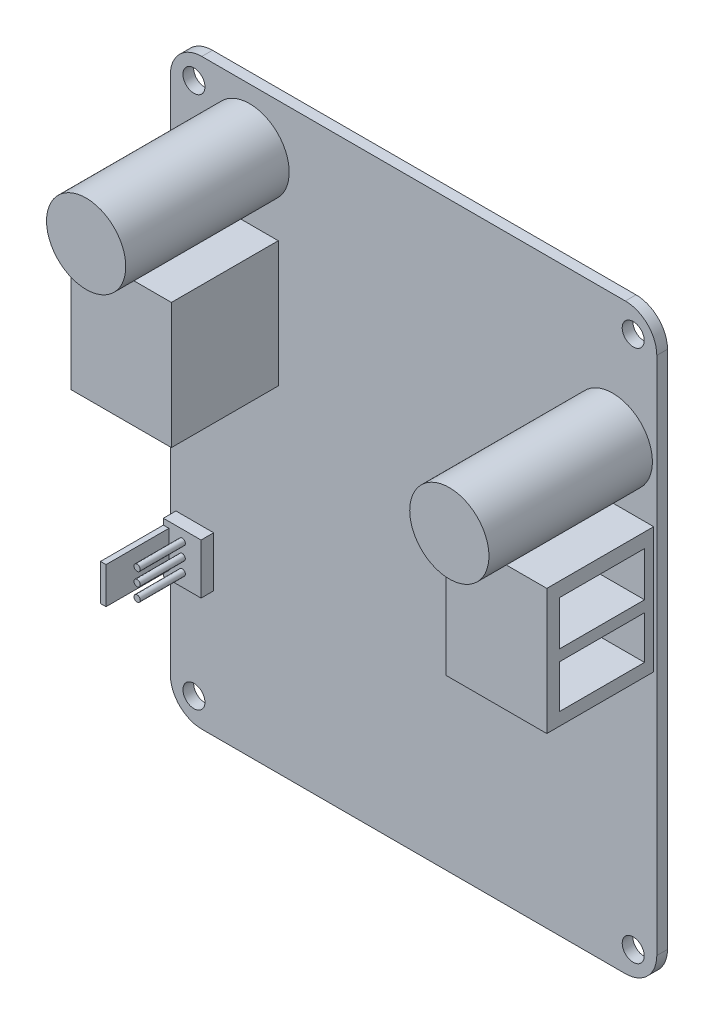
SolidWorks part; units mm, degrees
ref_plane "Front Plane" through (0, 0, 0) normal (0, 0, 1) x (1, 0, 0)
ref_plane "Top Plane" through (0, 0, 0) normal (0, 1, 0) x (1, 0, 0)
ref_plane "Right Plane" through (0, 0, 0) normal (1, 0, 0) x (0, 0, -1)
sketch "Sketch1" plane through (0, 0, 0) normal (0, 0, 1) x (1, 0, 0)
  line L0 (38.685, 92.67) -> (38.685, 0) construction
  line L1 (5, 0) -> (72.37, 0)
  line L2 (0, 5) -> (0, 87.67)
  line L3 (5, 92.67) -> (72.37, 92.67)
  line L4 (77.37, 5) -> (77.37, 87.67)
  line L6 (77.37, 46.335) -> (0, 46.335) construction
  circle A0 centre (73.62, 88.72) radius 1.75
  circle A1 centre (3.75, 88.72) radius 1.75
  circle A2 centre (3.75, 3.95) radius 1.75
  circle A3 centre (73.62, 3.95) radius 1.75
  arc A4 (77.37, 87.67) -> (72.37, 92.67) centre (72.37, 87.67) ccw
  arc A5 (72.37, 0) -> (77.37, 5) centre (72.37, 5) ccw
  arc A6 (5, 0) -> (0, 5) centre (5, 5) cw
  arc A7 (5, 92.67) -> (0, 87.67) centre (5, 87.67) ccw
  point P21 (77.37, 0)
  point P24 (0, 0)
  point P27 (0, 92.67)
  dimension "D3" = 3.95
  dimension "D4" = 3.5
  dimension "D5" = 3.75
  dimension "D6" = 5
  dimension "D1" = 92.67
  dimension "D2" = 77.37
extrude "Boss-Extrude1" add sketch "Sketch1" along normal blind 1.7
sketch "Sketch2" plane through (0, 0, 1.7) normal (0, 0, 1) x (1, 0, 0)
  line L0 (72.37, 92.67) -> (5, 92.67) construction
  line L1 (0, 87.67) -> (0, 5) construction
  line L2 (77.37, 5) -> (77.37, 87.67) construction
  circle A0 centre (12.6, 83.67) radius 6.3
  circle A1 centre (70.37, 72.67) radius 6.3
  dimension "D1" = 12.6
  dimension "D3" = 12.6
  dimension "D4" = 12.6
  dimension "D2" = 9
  dimension "D5" = 20
  dimension "D6" = 7
extrude "Boss-Extrude2" add sketch "Sketch2" along normal blind 26
sketch "Sketch3" plane through (0, 0, 1.7) normal (0, 0, 1) x (1, 0, 0)
  line L1 (60.8759, 63.8351) -> (76.8759, 63.8351)
  line L2 (60.8759, 63.8351) -> (60.8759, 43.8351)
  line L3 (60.8759, 43.8351) -> (76.8759, 43.8351)
  line L4 (76.8759, 63.8351) -> (76.8759, 43.8351)
  line L5 (1.1639, 73.3683) -> (17.1639, 73.3683)
  line L6 (1.1639, 73.3683) -> (1.1639, 53.3683)
  line L7 (1.1639, 53.3683) -> (17.1639, 53.3683)
  line L8 (17.1639, 73.3683) -> (17.1639, 53.3683)
  dimension "D1" = 20
  dimension "D2" = 16
  dimension "D3" = 20
  dimension "D4" = 16
extrude "Boss-Extrude3" add sketch "Sketch3" along normal blind 17
sketch "Sketch4" plane through (1.1639, 0, 0) normal (-1, 0, 0) x (0, 0, 1)
  line L1 (3.3693, 71.3508) -> (17.2233, 71.3508)
  line L2 (3.3693, 71.3508) -> (3.3693, 55.1184)
  line L3 (3.3693, 55.1184) -> (17.2233, 55.1184)
  line L4 (17.2233, 71.3508) -> (17.2233, 55.1184)
  line L5 (3.3693, 64.1288) -> (17.2233, 64.1288)
  line L6 (3.3693, 64.1288) -> (3.3693, 62.2855)
  line L7 (3.3693, 62.2855) -> (17.2233, 62.2855)
  line L8 (17.2233, 64.1288) -> (17.2233, 62.2855)
extrude "Cut-Extrude1" cut sketch "Sketch4" against normal blind 13 contours L2 L5 L4 L1 | L7 L2 L3 L4
sketch "Sketch5" plane through (76.8759, 0, 0) normal (1, 0, 0) x (0, 0, -1)
  line L1 (-16.6934, 61.5509) -> (-3.1539, 61.5509)
  line L2 (-16.6934, 61.5509) -> (-16.6934, 45.8623)
  line L3 (-16.6934, 45.8623) -> (-3.1539, 45.8623)
  line L4 (-3.1539, 61.5509) -> (-3.1539, 45.8623)
  line L5 (-16.6934, 54.4888) -> (-3.1539, 54.4888)
  line L6 (-16.6934, 54.4888) -> (-16.6934, 52.7121)
  line L7 (-16.6934, 52.7121) -> (-3.1539, 52.7121)
  line L8 (-3.1539, 54.4888) -> (-3.1539, 52.7121)
extrude "Cut-Extrude2" cut sketch "Sketch5" against normal blind 13 contours L2 L5 L4 L1 | L7 L2 L3 L4
sketch "Sketch6" plane through (0, 0, 1.7) normal (0, 0, 1) x (1, 0, 0)
  line L0 (5, 0) -> (72.37, 0) construction
  line L1 (0.8832, 28) -> (6.8832, 28)
  line L2 (0.8832, 28) -> (0.8832, 20)
  line L3 (0.8832, 20) -> (6.8832, 20)
  line L4 (6.8832, 28) -> (6.8832, 20)
  point P6 (0.8832, 28)
  dimension "D1" = 8
  dimension "D2" = 6
  dimension "D3" = 20
extrude "Boss-Extrude5" add sketch "Sketch6" along normal blind 12
sketch "Sketch7" plane through (0, 0, 13.7) normal (0, 0, 1) x (1, 0, 0)
  line L1 (0.8832, 28) -> (6.8832, 28)
  line L2 (0.8832, 28) -> (0.8832, 20)
  line L3 (0.8832, 20) -> (6.8832, 20)
  line L4 (6.8832, 28) -> (6.8832, 20)
  line L5 (0.8832, 27.0537) -> (1.7646, 27.0537)
  line L6 (0.8832, 27.0537) -> (0.8832, 21.2511)
  line L7 (0.8832, 21.2511) -> (1.7646, 21.2511)
  line L8 (1.7646, 27.0537) -> (1.7646, 21.2511)
  circle A0 centre (3.8832, 26.2657) radius 0.5
  circle A1 centre (3.8832, 24.1524) radius 0.5
  circle A2 centre (3.8832, 22.0391) radius 0.5
  line M1 (0.8832, 28) -> (0.8832, 20)
  line M2 (0.8832, 20) -> (6.8832, 20)
  line M3 (6.8832, 20) -> (6.8832, 28)
  line M4 (6.8832, 28) -> (0.8832, 28)
  dimension "D1" = 1
  dimension "D2" = 1
  dimension "D3" = 1
extrude "Cut-Extrude3" cut sketch "Sketch7" against normal blind 10 contours L5 L8 L7 A2 A1 A0 M1 M2 M3 M4
sketch "Sketch8" plane through (1.7646, 0, 0) normal (1, 0, 0) x (0, 0, -1)
  line L0 (-3.7, 27.0537) -> (-13.7, 27.0537) construction
  line L1 (-13.7, 21.2511) -> (-10.8737, 21.2511)
  line L2 (-13.7, 21.2511) -> (-13.7, 27.0537)
  line L3 (-13.7, 27.0537) -> (-10.8737, 27.0537)
  line L4 (-10.8737, 21.2511) -> (-10.8737, 27.0537)
extrude "Cut-Extrude4" cut sketch "Sketch8" along normal through all
